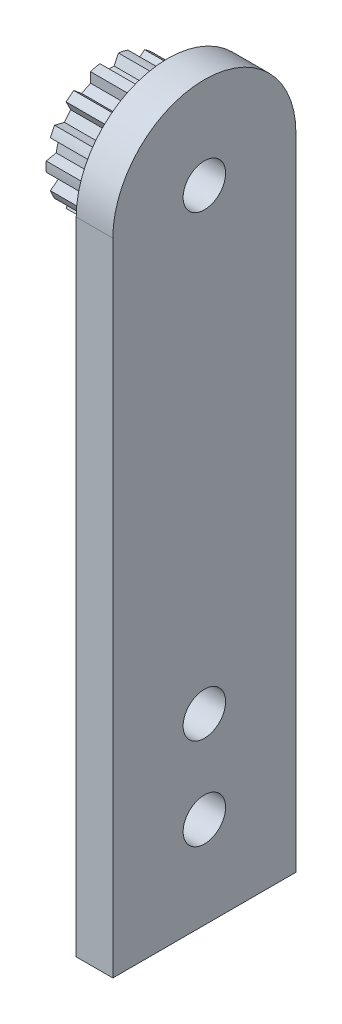
SolidWorks part; units mm, degrees
ref_plane "Front Plane" through (0, 0, 0) normal (0, 0, 1) x (1, 0, 0)
ref_plane "Top Plane" through (0, 0, 0) normal (0, 1, 0) x (1, 0, 0)
ref_plane "Right Plane" through (0, 0, 0) normal (1, 0, 0) x (0, 0, -1)
sketch "Sketch2" plane through (0, 0, 0) normal (1, 0, 0) x (0, 0, -1)
  line L3 (0, 0) -> (0, 3.7084) construction
  line L6 (0, -4.2164) -> (0, -4.5339) construction
  line L7 (-0.5715, 4.1775) -> (-0.3452, 3.6923)
  line L8 (0.5715, 4.1775) -> (0.3452, 3.6923)
  line L9 (-0.5715, 4.1775) -> (-0.6416, 4.3278)
  line L10 (0.5715, 4.1775) -> (0.6416, 4.3278)
  line L12 (-0.3452, 3.6923) -> (0.3452, 3.6923)
  line L14 (0, 4.2164) -> (0, 4.5339) construction
  line L15 (0, 0) -> (0, -1.143) construction
  circle A0 centre (0, 0) radius 4.5339 construction
  circle A1 centre (0, 0) radius 3.7084 construction
  circle A2 centre (0, 0) radius 4.2164 construction
  arc A7 (0.6416, 4.3278) -> (-0.6416, 4.3278) centre (0, 0) ccw
  point P5 (0, 4.3751)
  dimension "D3" = 0.3175
  dimension "D1" = 50
sketch "Sketch1" plane through (0, 0, 0) normal (0, 0, 1) x (1, 0, 0)
  line L0 (-5.5626, 0) -> (5.5626, 0) construction
  line L1 (-5.5626, 1.5875) -> (5.5626, 1.5875)
  line L2 (-5.5626, 1.5875) -> (-5.5626, 6.731)
  line L3 (-5.5626, 6.731) -> (-0.5969, 6.731)
  line L4 (-0.5969, 6.731) -> (0.4572, 5.6769)
  line L5 (0.4572, 5.6769) -> (0.4572, 4.5339)
  line L6 (0.4572, 4.5339) -> (4.5212, 4.5339)
  line L7 (4.5212, 4.5339) -> (4.5212, 5.1054)
  line L8 (4.5212, 4.5339) -> (5.5626, 4.5339) construction
  line L9 (5.0419, 6.731) -> (5.5626, 6.731)
  line L10 (5.5626, 6.731) -> (5.5626, 1.5875)
  line L11 (5.0419, 4.5339) -> (5.0419, 6.731) construction
  line L12 (-3.0797, 6.731) -> (-3.0797, 1.5875) construction
  arc A0 (4.5212, 5.1054) -> (5.0419, 6.731) centre (7.3191, 5.1054) cw
  dimension "Bore Size" = 3.175
  dimension "Overall Width" = 11.1252
  dimension "Inside Width" = 4.064
  dimension "Outside Width" = 5.1054
  dimension "Hub Dia" = 13.462
  dimension "OD" = 13.462
  dimension "D1" = 45
  dimension "D2" = 9.0678
  dimension "D3" = 1.143
  dimension "D4" = 0.5715
revolve "Revolve1" add sketch "Sketch1" angle 360 mid plane about L0
sketch "Sketch4" plane through (0.4572, 0, 0) normal (1, 0, 0) x (0, 0, -1)
  circle A0 centre (0, 0) radius 4.3751
  circle A1 centre (0, 0) radius 4.5339 construction
  circle A2 centre (0, 0) radius 4.5339
extrude "Cut-Extrude2" cut sketch "Sketch4" along normal up to surface (4.064 mm away) up to face at (4.5212, 0, 4.5339)
sketch "Sketch3" plane through (0.4572, 0, 0) normal (1, 0, 0) x (0, 0, -1)
  line L2 (-0.5715, 4.1775) -> (-0.3452, 3.6923) construction
  line L3 (-0.3452, 3.6923) -> (0.3452, 3.6923) construction
  line L4 (0.5715, 4.1775) -> (0.3452, 3.6923) construction
  line L5 (-0.6416, 4.3278) -> (-0.3452, 3.6923)
  line L6 (-0.3452, 3.6923) -> (0.3452, 3.6923)
  line L7 (0.6416, 4.3278) -> (0.3452, 3.6923)
  arc A1 (0.6416, 4.3278) -> (-0.6416, 4.3278) centre (0, 0) ccw construction
  arc A2 (0.6416, 4.3278) -> (-0.6416, 4.3278) centre (0, 0) ccw
extrude "Cut-Extrude1" cut sketch "Sketch3" along normal up to surface (4.064 mm away)
pattern_circular "CirPattern1" count 14 over 360 about axis through (0, 0, 0) along (1, 0, 0) of "Cut-Extrude1"
sketch "Sketch5" plane through (0, 0, 0) normal (0, 0, 1) x (1, 0, 0)
  line L1 (4.5212, 5.1054) -> (4.5212, -5.1054) construction
  point P0 (4.5212, 0)
sketch "Sketch6" plane through (0, 0, 0) normal (0, 1, 0) x (1, 0, 0)
  line L0 (-5.5626, 0) -> (-4.1402, 0) construction
  line L1 (-5.5626, 6.731) -> (-5.5626, -6.731) construction
  line L2 (0.4572, 0) -> (-0.9652, 0) construction
  line L3 (0.4572, -0.3452) -> (0.4572, 0.3452) construction
  circle A0 centre (-2.5527, 0) radius 1.5875
  dimension "D1" = 3.175
extrude "Cut-Extrude3" cut sketch "Sketch6" along normal through all
sketch "Sketch7" plane through (0, 0, 0) normal (0, 0, 1) x (1, 0, 0)
  line L0 (-3.7211, 6.731) -> (-2.5527, 6.731)
  line L1 (-3.9751, 6.477) -> (-3.9751, 2.2225)
  line L2 (-3.9751, 2.2225) -> (-3.7211, 1.9685)
  line L3 (-3.7211, 1.9685) -> (-2.5527, 1.9685)
  line L4 (-2.5527, 1.9685) -> (-2.5527, 6.731) construction
  line L6 (-3.9751, 6.477) -> (-3.7211, 6.731)
  line L7 (-5.5626, 6.731) -> (-0.5969, 6.731) construction
  line L8 (-2.5527, 6.731) -> (-2.5527, 1.9685)
  point P0 (-3.9751, 6.731)
  point P4 (-3.9751, 1.9685)
  dimension "D1" = 2.8448
  dimension "D2" = 0.381
revolve "Revolve2" add sketch "Sketch7" angle 360 mid plane about L4
sketch "Sketch8" plane through (0, 6.731, 0) normal (0, 1, 0) x (1, 0, 0)
  line L1 (-2.5527, 0.8212) -> (-3.2639, 0.4106)
  line L2 (-3.2639, 0.4106) -> (-3.2639, -0.4106)
  line L3 (-3.2639, -0.4106) -> (-2.5527, -0.8212)
  line L4 (-2.5527, -0.8212) -> (-1.8415, -0.4106)
  line L5 (-1.8415, -0.4106) -> (-1.8415, 0.4106)
  line L6 (-1.8415, 0.4106) -> (-2.5527, 0.8212)
  circle A0 centre (-2.5527, 0) radius 0.7112 construction
  dimension "D1" = 1.4224
extrude "Cut-Extrude4" cut sketch "Sketch8" against normal blind 1.016
pattern_circular "CirPattern2" [suppressed] count 2 over 90
pattern_circular "CirPattern3" [suppressed] count 2 over 90
sketch "Sketch11" plane through (4.5212, 0, 0) normal (-1, 0, 0) x (0, 0, 1)
  circle A1 centre (0, 0) radius 6.731
  circle A4 centre (0, 0) radius 6.731 construction
extrude "Cut-Extrude6" cut sketch "Sketch11" against normal blind 2.54
sketch "Sketch13" plane through (0.4572, 0, 0) normal (1, 0, 0) x (0, 0, -1)
  circle A0 centre (0, 0) radius 9.525
  dimension "D1" = 19.05
extrude "Cut-Extrude7" cut sketch "Sketch13" against normal through all
ref_plane "Plane1" through (2.4892, 0, 0) normal (-1, 0, 0) x (0, 0, 1)
sketch "Sketch17" plane through (0.4572, 0, 0) normal (-1, 0, 0) x (0, 0, 1)
  circle A0 centre (0, 0) radius 1.4732
  circle A1 centre (0, 0) radius 1.5875
  circle A2 centre (0, 0) radius 1.5875 construction
  dimension "D1" = 2.9464
extrude "Boss-Extrude2" add sketch "Sketch17" against normal up to surface (4.064 mm away) up to face at (4.5212, 0, 0)
sketch "Sketch12" plane through (4.5212, 0, 0) normal (1, 0, 0) x (0, 0, -1)
  line L0 (6.35, 0) -> (6.35, -44.45)
  line L1 (6.35, -44.45) -> (-6.35, -44.45)
  line L2 (-6.35, -44.45) -> (-6.35, 0)
  arc A0 (-6.35, 0) -> (6.35, 0) centre (0, 0) cw
  circle A2 centre (0, 0) radius 1.4732 construction
  circle A3 centre (0, 0) radius 1.4732
  dimension "D1" = 6.35
  dimension "D2" = 44.45
extrude "Boss-Extrude1" add sketch "Sketch12" along normal blind 2.54
mirror "Mirror1" [suppressed] about plane through (2.4892, 0, 0) normal (-1, 0, 0)
sketch "Sketch14" plane through (7.0612, 0, 0) normal (1, 0, 0) x (0, 0, -1)
  line L0 (0, 0) -> (0, -31.75)
  line L1 (0, -31.75) -> (0, -38.1)
  dimension "D1" = 31.75
  dimension "D2" = 6.35
hole_wizard "#4 Clearance Hole1" positions "Sketch15" profile "Sketch16" hole size "#4" standard "ANSI Inch" end condition through all
sketch "Sketch15" plane through (7.0612, 0, 0) normal (1, 0, 0) x (0, 0, -1)
  point P0 (0, -31.75)
  point P1 (0, -38.1)
sketch "Sketch16" plane through (7.0612, -31.75, 0) normal (0, 1, 0) x (0, 0, -1)
  line L0 (0, 0) -> (0, 6.604)
  line L1 (0, 6.604) -> (1.4732, 6.604)
  line L2 (1.4732, 6.604) -> (1.4732, 0)
  line L5 (1.4732, 0) -> (0, 0)
  line L11 (0, -6.35) -> (0, 107.95) construction
  dimension "Thru Hole Dia." = 2.9464
  dimension "Thru Hole Depth" = 6.604
equation "\"D3@Sketch2\" = (\"hs@Sketch2\"-\"ht@Sketch2\")/2"
equation "\"D2@Sketch1\" = \"PD@Sketch2\""
equation "\"D3@Sketch1\" = \"hs@Sketch2\""
equation "\"D4@Sketch1\" = \"D3@Sketch1\"/2"
